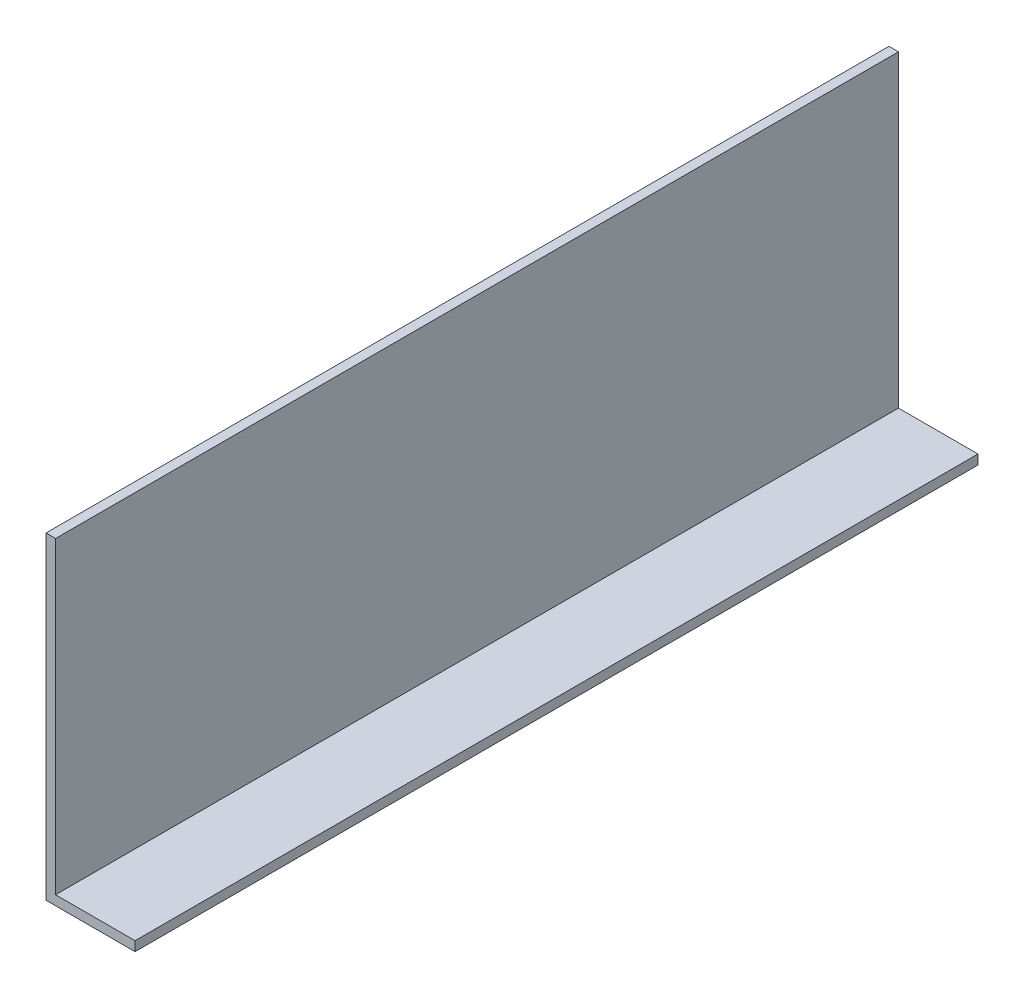
SolidWorks part; units mm, degrees
ref_plane "Front Plane" through (0, 0, 0) normal (0, 0, 1) x (1, 0, 0)
ref_plane "Top Plane" through (0, 0, 0) normal (0, 1, 0) x (1, 0, 0)
ref_plane "Right Plane" through (0, 0, 0) normal (1, 0, 0) x (0, 0, -1)
sketch "Sketch1" plane through (0, 0, 0) normal (1, 0, 0) x (0, 0, -1)
  line L1 (-265, 100) -> (265, 100)
  line L2 (-265, 100) -> (-265, -100)
  line L3 (-265, -100) -> (265, -100)
  line L4 (265, 100) -> (265, -100)
  line L5 (-265, 100) -> (265, -100) construction
  line L6 (-265, -100) -> (265, 100) construction
  point P0 (0, 0)
  dimension "D1" = 200
  dimension "D2" = 530
extrude "Boss-Extrude1" add sketch "Sketch1" along normal mid plane 6 contours L1 L4 L3 L2
sketch "Sketch2" plane through (3, 0, 0) normal (1, 0, 0) x (0, 0, -1)
  line L0 (265, 100) -> (265, -100) construction
  line L1 (-265, -100) -> (265, -100)
  line L2 (-265, -100) -> (-265, -94)
  line L3 (-265, -94) -> (265, -94)
  line L4 (265, -100) -> (265, -94)
  dimension "D1" = 6
extrude "Boss-Extrude2" add sketch "Sketch2" along normal blind 50
